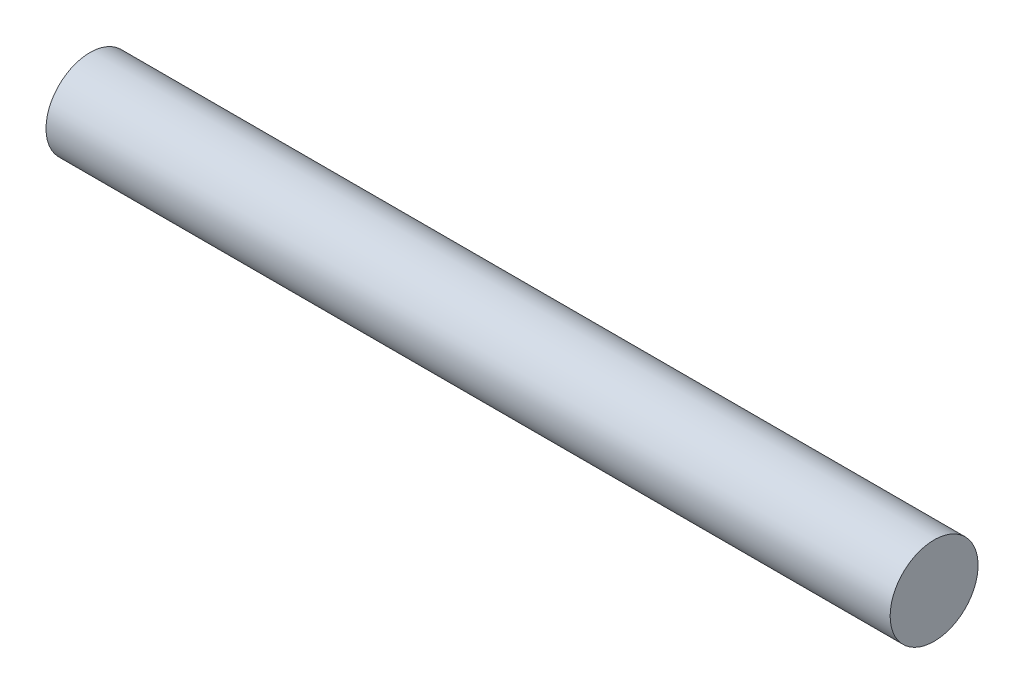
SolidWorks part; units mm, degrees
ref_plane "Front Plane" through (0, 0, 0) normal (0, 0, 1) x (1, 0, 0)
ref_plane "Top Plane" through (0, 0, 0) normal (0, 1, 0) x (1, 0, 0)
ref_plane "Right Plane" through (0, 0, 0) normal (1, 0, 0) x (0, 0, -1)
sketch "Sketch2" plane through (0, 0, 0) normal (1, 0, 0) x (0, 0, -1)
  circle A0 centre (0, 0) radius 15.875
  dimension "D1" = 31.75
extrude "Boss-Extrude1" add sketch "Sketch2" along normal blind 76.2 contours A0
sketch "Sketch3" plane through (76.2, 0, 0) normal (1, 0, 0) x (0, 0, -1)
  circle A0 centre (0, 0) radius 15.875
  dimension "D1" = 31.75
extrude "Boss-Extrude2" add sketch "Sketch3" along normal blind 228.6
